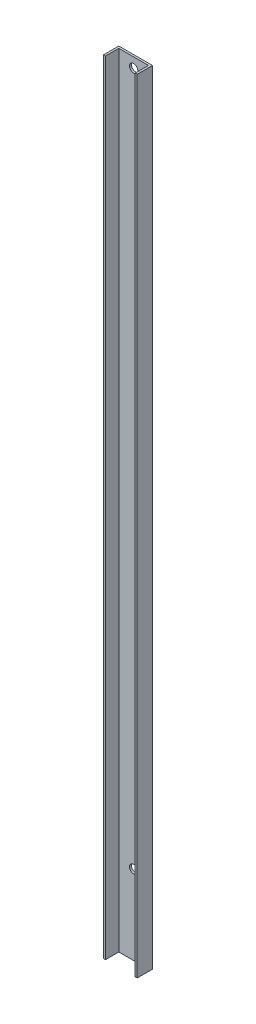
SolidWorks part; units mm, degrees
ref_plane "Front Plane" through (0, 0, 0) normal (0, 0, 1) x (1, 0, 0)
ref_plane "Top Plane" through (0, 0, 0) normal (0, 1, 0) x (1, 0, 0)
ref_plane "Right Plane" through (0, 0, 0) normal (1, 0, 0) x (0, 0, -1)
sketch "Sketch1" plane through (0, 0, 0) normal (0, 1, 0) x (1, 0, 0)
  line L0 (-10.9455, 0) -> (-10.9455, 7.7)
  line L1 (-10.9455, 7.7) -> (6.0545, 7.7)
  line L2 (6.0545, 7.7) -> (6.0545, 0)
  dimension "D1" = 7.7
  dimension "D2" = 17
extrude "Extrude-Thin1" add sketch "Sketch1" along normal blind 430 thin
sketch "Sketch2" plane through (0, 0, -6.7) normal (0, 0, 1) x (1, 0, 0)
  line L0 (6.0545, 430) -> (6.0545, 0) construction
  line L1 (-9.9455, 430) -> (5.0545, 430) construction
  line L2 (80.2435, 215) -> (-35.0705, 215) construction
  line L3 (-9.9455, 0) -> (5.0545, 0) construction
  circle A0 centre (-2.4455, 390) radius 2.1
  circle A1 centre (-2.4455, 40) radius 2.1
  dimension "D3" = 4.2
  dimension "D1" = 8.5
  dimension "D2" = 40
  dimension "D4" = 215
extrude "Cut-Extrude1" cut sketch "Sketch2" against normal blind 10
sketch "Sketch3" plane through (0, 0, 0) normal (0, 0, 1) x (1, 0, 0)
  line L0 (-9.9455, 430) -> (5.0545, 430) construction
  line L1 (-18.7931, 437.5268) -> (9.0847, 437.5268)
  line L2 (-18.7931, 437.5268) -> (-18.7931, 395)
  line L3 (-18.7931, 395) -> (9.0847, 395)
  line L4 (9.0847, 437.5268) -> (9.0847, 395)
  dimension "D1" = 35
extrude "Cut-Extrude2" cut sketch "Sketch3" against normal blind 10
